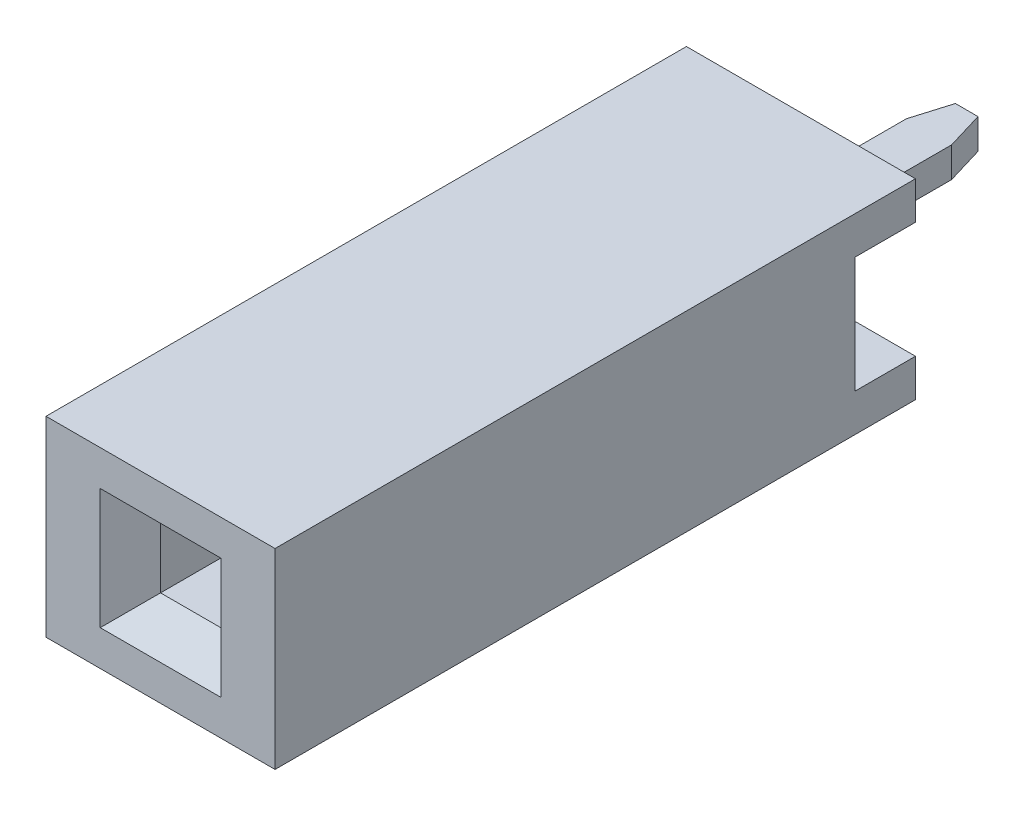
SolidWorks part; units mm, degrees
ref_plane "Front Plane" through (0, 0, 0) normal (0, 0, 1) x (1, 0, 0)
ref_plane "Top Plane" through (0, 0, 0) normal (0, 1, 0) x (1, 0, 0)
ref_plane "Right Plane" through (0, 0, 0) normal (1, 0, 0) x (0, 0, -1)
sketch "Sketch1" plane through (0, 0, 0) normal (1, 0, 0) x (0, -1, 0)
  line L0 (0, 0) -> (0, -8.5) construction
  line L1 (-1.27, 0) -> (1.27, 0)
  line L2 (-1.27, 0) -> (-1.27, -8.5)
  line L3 (-1.27, -8.5) -> (1.27, -8.5)
  line L4 (1.27, 0) -> (1.27, -8.5)
  point P0 (0, 0)
  dimension "D1" = 2.54
  dimension "D2" = 8.5
extrude "Boss-Extrude1" add sketch "Sketch1" along normal mid plane 3.04
sketch "Эскиз1" plane through (1.52, 0, 0) normal (1, 0, 0) x (0, 0, -1)
  line L0 (0, -0.77) -> (-0.8, -0.77)
  line L1 (0, -1.27) -> (0, 1.27) construction
  line L2 (-0.8, -0.77) -> (-0.8, 0.77)
  line L4 (-0.8, 0.77) -> (0, 0.77)
  line L5 (0, 0.77) -> (0, -0.77)
  line L6 (-8.5, -1.27) -> (0, -1.27) construction
  dimension "D1" = 0.5
  dimension "D2" = 0.8
  dimension "D3" = 0.5
extrude "Вырез-Вытянуть1" cut sketch "Эскиз1" against normal through all
sketch "Sketch2" plane through (0, 0, 8.5) normal (0, 0, 1) x (-1, 0, 0)
  line L0 (0, -1.27) -> (0, 1.27) construction
  line L3 (-1.52, -1.27) -> (1.52, -1.27) construction
  line L4 (-0.4, 0.4) -> (0.4, 0.4)
  line L5 (-0.4, 0.4) -> (-0.4, -0.4)
  line L6 (-0.4, -0.4) -> (0.4, -0.4)
  line L7 (0.4, 0.4) -> (0.4, -0.4)
  line L8 (-0.4, 0.4) -> (0.4, -0.4) construction
  line L9 (-0.4, -0.4) -> (0.4, 0.4) construction
  line L10 (-1.52, 1.27) -> (1.52, 1.27) construction
  point P5 (0, 0)
  dimension "D1" = 0.8
extrude "Cut-Extrude1" cut sketch "Sketch2" against normal offset from surface (7 mm away) 0.7 up to face at (0, 0, 0.8)
chamfer "Фаска1" distance 0.4 angle 45 4 edges at (0, -0.4, 8.5) (0.4, 0, 8.5) (0, 0.4, 8.5) (-0.4, 0, 8.5)
sketch "Sketch3" plane through (0, 0, 0) normal (0, 1, 0) x (1, 0, 0)
  line L0 (-0.3, 0) -> (-0.3, 1.7)
  line L1 (0.3, 0) -> (0.3, -0.8)
  line L2 (-0.3, 1.7) -> (-0.15, 2.2)
  line L3 (-0.15, 2.2) -> (0.15, 2.2)
  line L4 (0, 2.2) -> (0, 0) construction
  line L5 (-0.3, 0) -> (0.3, 0) construction
  line L6 (0.3, 1.7) -> (0.15, 2.2)
  line L7 (0.3, 0) -> (0.3, 1.7)
  line L8 (0.3, -0.8) -> (-0.3, -0.8)
  line L9 (-0.3, -0.8) -> (-0.3, 0)
  line L10 (-1.52, -0.8) -> (1.52, -0.8) construction
  line L11 (0.3, 1.7) -> (-0.3, 1.7) construction
  line L12 (0.4, -1.5) -> (-0.4, -1.5)
  line L13 (-0.4, -1.5) -> (-0.4, -6.9)
  line L14 (-0.4, -6.9) -> (-0.3, -6.9)
  line L15 (-0.3, -6.9) -> (-0.3, -1.6)
  line L16 (-0.3, -1.6) -> (0.3, -1.6)
  line L17 (0.3, -1.6) -> (0.3, -6.9)
  line L18 (0.3, -6.9) -> (0.4, -6.9)
  line L19 (0.4, -6.9) -> (0.4, -1.5)
  line L20 (-0.4, -1.5) -> (-0.4, -8.1) construction
  line L21 (0.4, -1.5) -> (0.4, -8.1) construction
  line L22 (0.4, -1.5) -> (-0.4, -1.5) construction
  dimension "D1" = 0.6
  dimension "D2" = 0.3
  dimension "D3" = 2.2
  dimension "D4" = 0.5
  dimension "D5" = 1.6
  dimension "D6" = 0.1
  dimension "D7" = 0.1
extrude "Boss-Extrude2" add sketch "Sketch3" along normal mid plane 0.4
pattern_linear "LPattern1" [suppressed] count 3 spacing 2.54
combine bodies "Соединить1" [suppressed] operation type add bodies to combine 107 104 103 108
